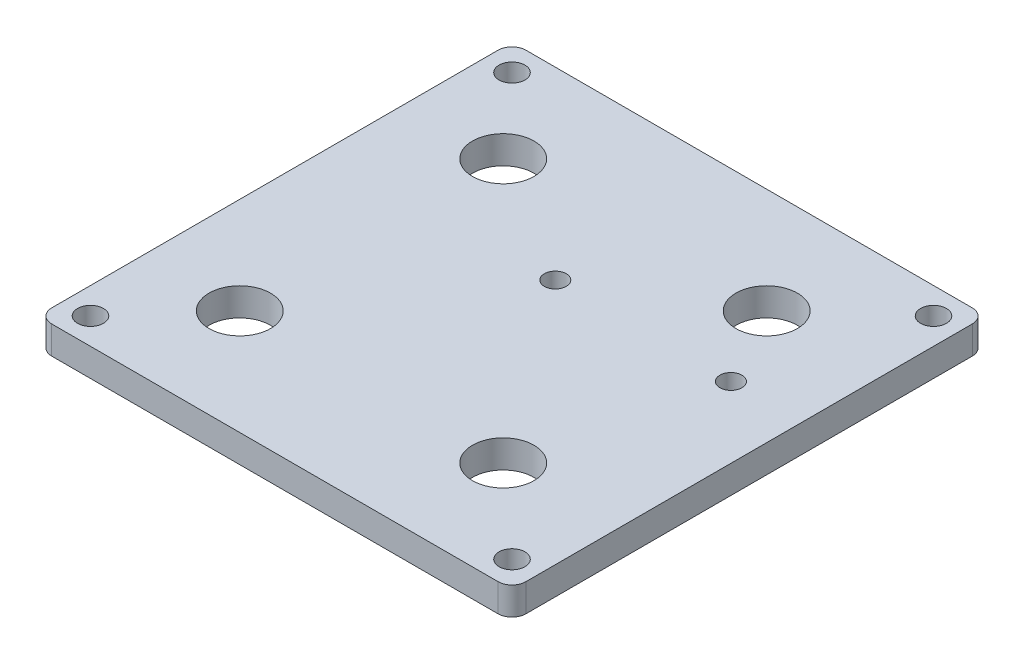
SolidWorks part; units mm, degrees
material "AISI 4130 Steel, annealed at 865C"
ref_plane "Front Plane" through (0, 0, 0) normal (0, 0, 1) x (1, 0, 0)
ref_plane "Top Plane" through (0, 0, 0) normal (0, 1, 0) x (1, 0, 0)
ref_plane "Right Plane" through (0, 0, 0) normal (1, 0, 0) x (0, 0, -1)
sketch "Sketch1" plane through (0, 0, 0) normal (0, 1, 0) x (1, 0, 0)
  line L0 (5, -7) -> (5, -37) construction
  line L1 (0, 0) -> (42, 0)
  line L2 (0, 0) -> (0, -44)
  line L3 (0, -44) -> (42, -44)
  line L4 (42, 0) -> (42, -44)
  line L5 (35, -7) -> (5, -7) construction
  line L6 (19.93, -16) -> (39.93, -16) construction
  line L7 (21, 0) -> (21, -44) construction
  line L8 (42, 0) -> (49.18, 0)
  line L9 (49.18, 0) -> (49.18, -44)
  line L10 (49.18, -44) -> (42, -44)
  line L11 (21, -22) -> (-15.2405, -22) construction
  line L12 (38, 2.5) -> (38, 0) construction
  line L13 (0, 0) -> (42, 0)
  line L14 (0, 0) -> (0, 5)
  line L15 (0, 5) -> (42, 5)
  line L16 (42, 0) -> (42, 5)
  line L17 (0, -44) -> (42, -44)
  line L18 (0, -44) -> (0, -49)
  line L19 (0, -49) -> (42, -49)
  line L20 (42, -44) -> (42, -49)
  line L21 (38, -46.5) -> (38, -44) construction
  circle A0 centre (5, -7) radius 3.5
  circle A1 centre (35, -7) radius 3.5
  circle A2 centre (35, -37) radius 3.5
  circle A3 centre (5, -37) radius 3.5
  circle A4 centre (19.93, -16) radius 0.5
  circle A5 centre (39.93, -16) radius 0.5
  circle A6 centre (4, 2.5) radius 0.5 construction
  circle A7 centre (38, 2.5) radius 0.5 construction
  circle A8 centre (38, -46.5) radius 0.5 construction
  circle A9 centre (4, -46.5) radius 0.5 construction
  dimension "D1" = 7
  dimension "D2" = 1
  dimension "D14" = 1
  dimension "D3" = 30
  dimension "D4" = 30
  dimension "D5" = 20
  dimension "D6" = 42
  dimension "D7" = 44
  dimension "D8" = 7
  dimension "D9" = 7
  dimension "D10" = 1.07
  dimension "D11" = 7.18
  dimension "D12" = 6
  dimension "D13" = 5
  dimension "D15" = 4
  dimension "D16" = 4
  dimension "D17" = 2.5
extrude "Boss-Extrude1" add sketch "Sketch1" along normal blind 3.175 contours L4 L1 L2 L3 A5 A4 A3 A2 A1 A0 | L1 L16 L15 L14 | L20 L3 L18 L19
sketch "Sketch3" plane through (0, 3.175, 0) normal (0, 1, 0) x (1, 0, 0)
  line L0 (42, 5) -> (42, -49) construction
  line L1 (0, 5) -> (-6, 5)
  line L2 (0, 5) -> (0, -49)
  line L3 (0, -49) -> (-6, -49)
  line L4 (-6, 5) -> (-6, -49)
  line L5 (42, 5) -> (48, 5)
  line L6 (42, 5) -> (42, -49)
  line L7 (42, -49) -> (48, -49)
  line L8 (48, 5) -> (48, -49)
  circle A0 centre (-3, 2) radius 1.4732
  circle A1 centre (-3, -46) radius 1.4732
  circle A2 centre (45, -46) radius 1.4732
  circle A3 centre (45, 2) radius 1.4732
  point P10 (-3, -46)
  point P12 (45, -46)
  point P14 (-3, 2)
  point P15 (45, 2)
  point P27 (-3, -46)
  dimension "D6" = 2.9464
  dimension "D1" = 6
  dimension "D2" = 3
  dimension "D3" = 3
  dimension "D4" = 3
  dimension "D5" = 3
extrude "Boss-Extrude2" add sketch "Sketch3" against normal up to surface (3.175 mm away) up to face at (21, 0, 22)
hole_wizard "M3x0.5 Tapped Hole1" positions "3DSketch1" profile "Sketch2" tap size "M3x0.5" standard "ANSI Metric" end condition through all
sketch3d "3DSketch1"
  circle A2 centre (39.93, 3.175, 16) radius 0.5 construction
  circle A3 centre (19.93, 3.175, 16) radius 0.5 construction
  point P0 (39.93, 3.175, 16)
  point P2 (19.93, 3.175, 16)
  point P17 (39.93, 3.675, 16)
  point P25 (19.93, 3.675, 16)
sketch "Sketch2" plane through (39.93, 3.175, 16) normal (1, 0, 0) x (0, 0, 1)
  line L0 (0, 0) -> (0, 3.175)
  line L1 (0, 3.175) -> (1.25, 3.175)
  line L2 (1.25, 3.175) -> (1.25, 0)
  line L5 (1.25, 0) -> (0, 0)
  line L11 (0, -6.35) -> (0, 107.95) construction
  dimension "Thru Tap Drill Dia." = 2.5
  dimension "Thru Tap Drill Depth" = 3.175
cosmetic thread "Hole Thread9" parameters "D2"=3
cosmetic thread "Hole Thread10" parameters "D2"=3
fillet "Fillet1" radius 1.5875 4 edges at (48, 1.5875, -5) (48, 1.5875, 49) (-6, 1.5875, 49) (-6, 1.5875, -5)
equation "\"D8@Sketch1\"=(\"D7@Sketch1\"-\"D4@Sketch1\")/2"
equation "\"D9@Sketch1\"=\"D8@Sketch1\""
equation "\"D10@Sketch1\"=9.37mm-6.3-2-0.14+0.58-0.44"
equation "\"D3@Sketch3\"=\"D2@Sketch3\""
equation "\"D4@Sketch3\"=\"D3@Sketch3\""
equation "\"D5@Sketch3\"=\"D2@Sketch3\""
equation "\"D16@Sketch1\"=\"D15@Sketch1\""
equation "\"D17@Sketch1\"=\"D13@Sketch1\"/2"
